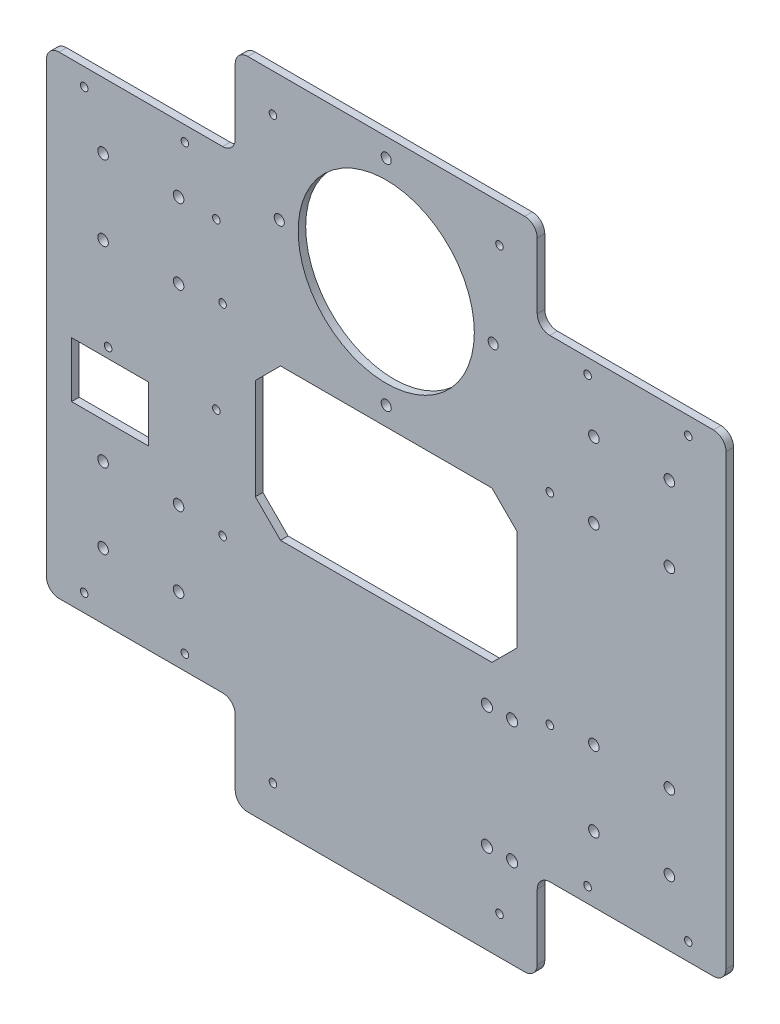
SolidWorks part; units mm, degrees
ref_plane "前视基准面" through (0, 0, 0) normal (0, 0, 1) x (1, 0, 0)
ref_plane "上视基准面" through (0, 0, 0) normal (0, 1, 0) x (1, 0, 0)
ref_plane "右视基准面" through (0, 0, 0) normal (1, 0, 0) x (0, 0, -1)
other "Configuration Table"
sketch "草图1" plane through (0, 0, 0) normal (0, 0, 1) x (1, 0, 0)
  line L1 (-135, -130) -> (135, -130)
  line L2 (-135, -130) -> (-135, 130)
  line L3 (-135, 130) -> (135, 130)
  line L4 (135, -130) -> (135, 130)
  line L5 (-135, -130) -> (135, 130) construction
  line L6 (-135, 130) -> (135, -130) construction
  point P0 (0, 0)
  dimension "D1" = 260
  dimension "D2" = 270
extrude "凸台-拉伸1" add sketch "草图1" along normal blind 3
sketch "草图2" plane through (0, 0, 3) normal (0, 0, 1) x (1, 0, 0)
  line L0 (-168.582, 0) -> (189.3742, 0) construction
  line L1 (135, -130) -> (60, -130)
  line L2 (135, -130) -> (135, -94)
  line L3 (135, -94) -> (60, -94)
  line L4 (60, -130) -> (60, -94)
  line L5 (0, 167.1918) -> (0, -215.3692) construction
  line L6 (-60, -130) -> (-60, -94)
  line L7 (-135, -94) -> (-60, -94)
  line L8 (-135, -130) -> (-135, -94)
  line L9 (-135, -130) -> (-60, -130)
  line L10 (-135, 130) -> (-60, 130)
  line L11 (-135, 130) -> (-135, 94)
  line L12 (-135, 94) -> (-60, 94)
  line L13 (-60, 130) -> (-60, 94)
  line L14 (60, 130) -> (60, 94)
  line L15 (135, 94) -> (60, 94)
  line L16 (135, 130) -> (135, 94)
  line L17 (135, 130) -> (60, 130)
  dimension "D1" = 36
  dimension "D2" = 75
extrude "切除-拉伸1" cut sketch "草图2" against normal up to next
fillet "圆角1" radius 5 12 edges at (-135, 94, 1.5) (-60, 94, 1.5) (-60, 130, 1.5) (60, 130, 1.5) (60, 94, 1.5) (135, 94, 1.5) (135, -94, 1.5) (60, -94, 1.5) (60, -130, 1.5) (-60, -130, 1.5) (-60, -94, 1.5) (-135, -94, 1.5)
sketch "草图3" plane through (0, 0, 3) normal (0, 0, 1) x (1, 0, 0)
  line L0 (55, 130) -> (-55, 130) construction
  circle A0 centre (0, 80) radius 35
  dimension "D1" = 70
  dimension "D2" = 50
extrude "切除-拉伸2" cut sketch "草图3" against normal blind 10
sketch "草图4" plane through (0, 0, 0) normal (0, 0, -1) x (-1, 0, 0)
  line L0 (-166.6705, 0) -> (225.4181, 0) construction
  line L1 (0, 164.6563) -> (0, -204.1035) construction
  circle A0 centre (-112.5, -38.1) radius 2.1
  circle A1 centre (-112.5, -67.9) radius 2.1
  circle A2 centre (-82.5, -38.1) radius 2.1
  circle A3 centre (-82.5, -67.9) radius 2.1
  circle A4 centre (-82.5, 67.9) radius 2.1
  circle A5 centre (-82.5, 38.1) radius 2.1
  circle A6 centre (-112.5, 67.9) radius 2.1
  circle A7 centre (-112.5, 38.1) radius 2.1
  circle A8 centre (112.5, 38.1) radius 2.1
  circle A9 centre (112.5, 67.9) radius 2.1
  circle A10 centre (82.5, 38.1) radius 2.1
  circle A11 centre (82.5, 67.9) radius 2.1
  circle A12 centre (82.5, -67.9) radius 2.1
  circle A13 centre (82.5, -38.1) radius 2.1
  circle A14 centre (112.5, -67.9) radius 2.1
  circle A15 centre (112.5, -38.1) radius 2.1
extrude "切除-拉伸3" cut sketch "草图4" against normal blind 4.55
sketch "草图5" plane through (0, 0, 0) normal (0, 0, -1) x (-1, 0, 0)
  line L0 (0, 179.4717) -> (0, -161.0395) construction
  circle A0 centre (45, 115) radius 1.5
  circle A1 centre (120, 87) radius 1.5
  circle A2 centre (120, -87) radius 1.5
  circle A3 centre (45, -115) radius 1.5
  circle A4 centre (65, -40) radius 1.5
  circle A5 centre (65, 40) radius 1.5
  circle A6 centre (-65, 40) radius 1.5
  circle A7 centre (-65, -40) radius 1.5
  circle A8 centre (-45, -115) radius 1.5
  circle A9 centre (-120, -87) radius 1.5
  circle A10 centre (-120, 87) radius 1.5
  circle A11 centre (-45, 115) radius 1.5
  circle A12 centre (-50, -94.25) radius 2.2
  circle A13 centre (-40, -94.25) radius 2.2
  circle A14 centre (-50, -45.75) radius 2.2
  circle A15 centre (-40, -45.75) radius 2.2
  dimension "D1" = 3
extrude "切除-拉伸4" cut sketch "草图5" against normal through all
sketch "草图6" plane through (0, 0, 3) normal (0, 0, 1) x (1, 0, 0)
  circle A0 centre (-110.5, 2.25) radius 1.5
  circle A1 centre (-67.5, 2.25) radius 1.5
  circle A2 centre (-67.5, 67.75) radius 1.5
  dimension "D1" = 3
  dimension "D2" = 3
  dimension "D3" = 3
extrude "切除-拉伸5" cut sketch "草图6" against normal through all
sketch "草图7" plane through (0, 0, 0) normal (0, 0, -1) x (-1, 0, 0)
  line L0 (0, 169.6728) -> (0, -174.2825) construction
  line L1 (-186.6932, 0) -> (265.0583, 0) construction
  circle A0 centre (80, 88) radius 1.5
  circle A2 centre (-80, 88) radius 1.5
  circle A3 centre (80, -88) radius 1.5
  circle A4 centre (-80, -88) radius 1.5
  dimension "D1" = 88
  dimension "D2" = 80
  dimension "D3" = 3
extrude "切除-拉伸6" cut sketch "草图7" against normal through all
sketch "草图8" plane through (0, 0, 0) normal (0, 0, -1) x (-1, 0, 0)
  line L5 (-50, -35) -> (-50, 65) construction
  line L6 (-52, -30) -> (52, -30)
  line L7 (-52, -30) -> (-52, 30)
  line L8 (-52, 30) -> (52, 30)
  line L9 (52, -30) -> (52, 30)
  line L10 (50, 65) -> (50, -35) construction
  line L11 (50, -35) -> (-50, -35) construction
  line L12 (-50, 65) -> (50, 65) construction
  dimension "D1" = 2
  dimension "D2" = 2
  dimension "D3" = 5
  dimension "D4" = 35
extrude "切除-拉伸7" cut sketch "草图8" against normal through all
chamfer "倒角1" distance 10 angle 45 4 edges at (-52, 30, 1.5) (-52, -30, 1.5) (52, 30, 1.5) (52, -30, 1.5)
sketch "草图9" plane through (0, 0, 3) normal (0, 0, 1) x (1, 0, 0)
  circle A0 centre (42.5, 80) radius 2
  circle A1 centre (0, 37.5) radius 2
  circle A2 centre (-42.5, 80) radius 2
  circle A3 centre (0, 122.5) radius 2
  dimension "D1" = 4
  dimension "D2" = 4
  dimension "D3" = 4
  dimension "D4" = 4
extrude "切除-拉伸8" cut sketch "草图9" against normal through all
sketch "草图11" plane through (0, 0, 0) normal (0, 0, -1) x (-1, 0, 0)
  line L0 (135, 89) -> (135, -89) construction
  line L1 (94.5, -1.7615) -> (125, -1.7615)
  line L2 (94.5, -1.7615) -> (94.5, -23.7615)
  line L3 (94.5, -23.7615) -> (125, -23.7615)
  line L4 (125, -1.7615) -> (125, -23.7615)
  point P4 (92.0906, -25.1457)
  point P5 (124.0084, 28.6416)
  point P8 (125, -1.7615)
  dimension "D1" = 30.5
  dimension "D2" = 22
  dimension "D3" = 10
extrude "切除-拉伸9" cut sketch "草图11" against normal up to next
